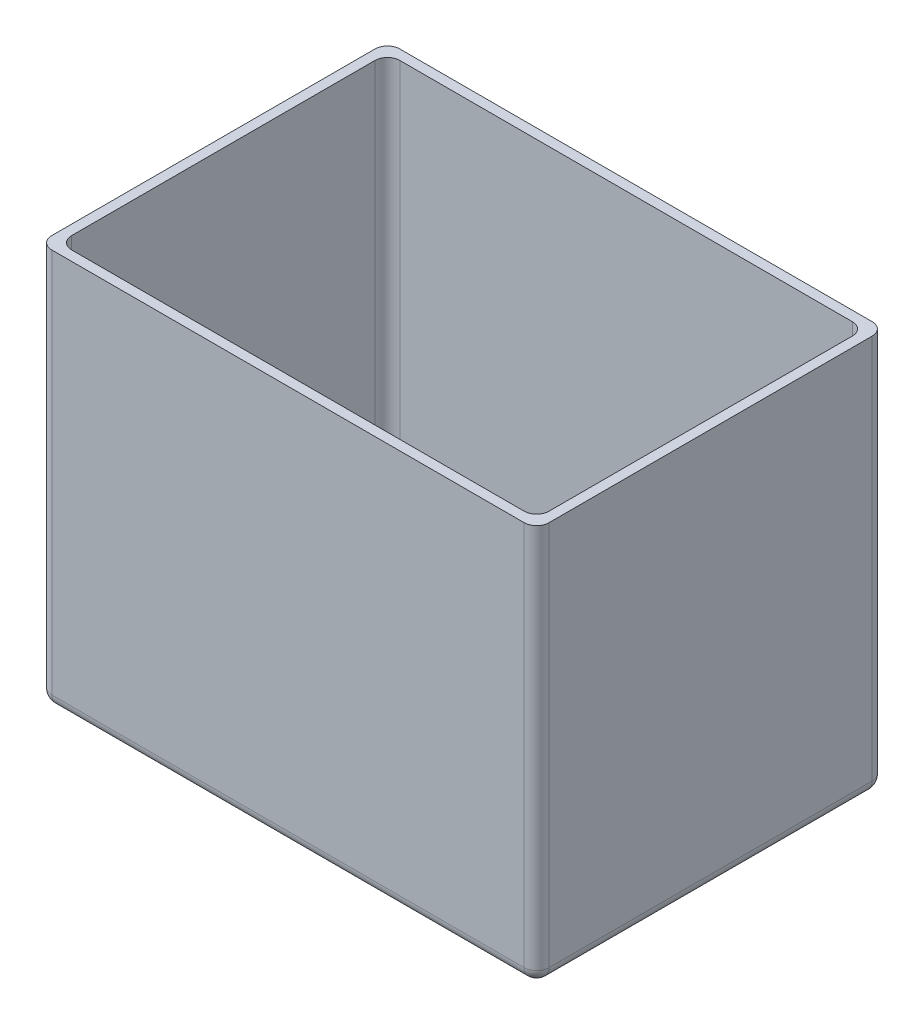
SolidWorks part; units mm, degrees
ref_plane "Спереди" through (0, 0, 0) normal (0, 0, 1) x (1, 0, 0)
ref_plane "Сверху" through (0, 0, 0) normal (0, 1, 0) x (1, 0, 0)
ref_plane "Справа" through (0, 0, 0) normal (1, 0, 0) x (0, 0, -1)
sketch "Эскиз2" plane through (0, 0, 0) normal (0, 1, 0) x (1, 0, 0)
  line L1 (-50, 35) -> (50, 35)
  line L2 (-50, 35) -> (-50, -35)
  line L3 (-50, -35) -> (50, -35)
  line L4 (50, 35) -> (50, -35)
  line L5 (-50, 35) -> (50, -35) construction
  line L6 (-50, -35) -> (50, 35) construction
  point P0 (0, 0)
  point P6 (0, 0)
extrude "Бобышка-Вытянуть1" add sketch "Эскиз2" along normal blind 80
sketch "Эскиз4" plane through (0, 80, 0) normal (0, 1, 0) x (1, 0, 0)
  line L1 (48, -33) -> (-48, -33)
  line L2 (48, -33) -> (48, 33)
  line L3 (48, 33) -> (-48, 33)
  line L4 (-48, -33) -> (-48, 33)
  line L5 (48, -33) -> (-48, 33) construction
  line L6 (48, 33) -> (-48, -33) construction
  point P0 (0, 0)
  point P6 (0, 0)
extrude "Вырез-Вытянуть1" cut sketch "Эскиз4" against normal blind 78
fillet "Скругление2" radius 2.5 16 edges at (-50, 0, 0) (-50, 40, -35) (0, 0, -35) (50, 40, -35) (50, 0, 0) (50, 40, 35) (0, 0, 35) (-50, 40, 35) (48, 41, -33) (-48, 41, 33) (0, 2, 33) (48, 41, 33) (48, 2, 0) (0, 2, -33) (-48, 41, -33) (-48, 2, 0)
sketch "Эскиз6" plane through (0, 2, 0) normal (0, 1, 0) x (1, 0, 0)
  circle A0 centre (-37.5, 13.725) radius 5
  circle A1 centre (37.5, 13.725) radius 5
  circle A2 centre (-37.5, -13.725) radius 5
  circle A3 centre (37.5, -13.725) radius 5
  circle A4 centre (-37.5, 13.725) radius 2.3
  circle A5 centre (-37.5, -13.725) radius 2.3
  circle A6 centre (37.5, -13.725) radius 2.3
  circle A7 centre (37.5, 13.725) radius 2.3
extrude "Бобышка-Вытянуть3" add sketch "Эскиз6" along normal blind 10
